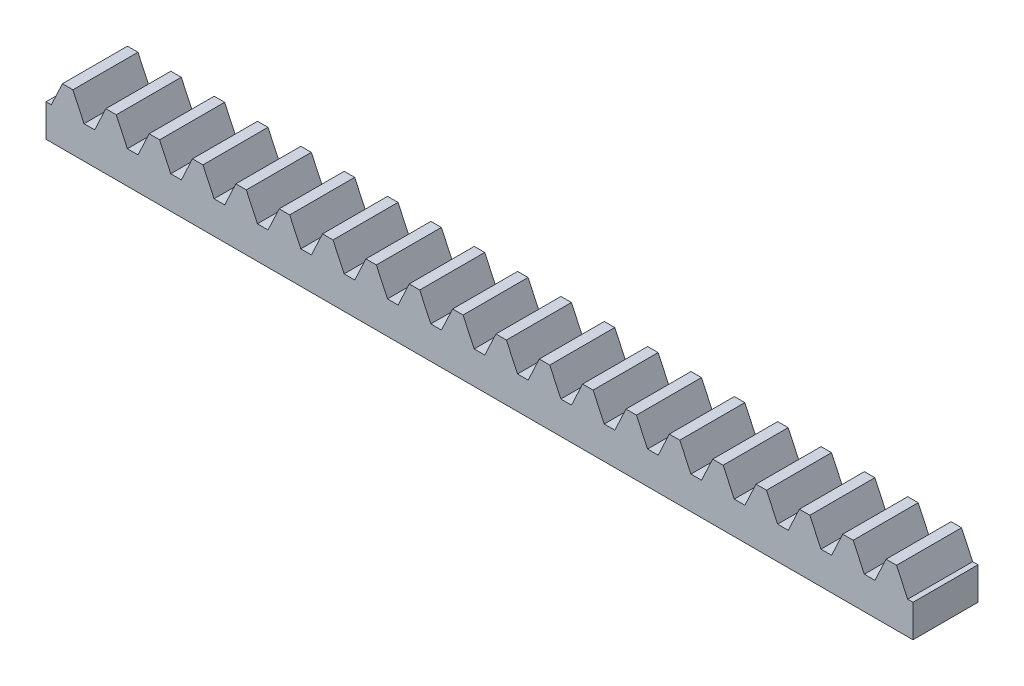
SolidWorks part; units mm, degrees
material "ABS"
ref_plane "Front Plane" through (0, 0, 0) normal (0, 0, 1) x (1, 0, 0)
ref_plane "Top Plane" through (0, 0, 0) normal (0, 1, 0) x (1, 0, 0)
ref_plane "Right Plane" through (0, 0, 0) normal (1, 0, 0) x (0, 0, -1)
sketch "Sketch1" plane through (0, 0, 0) normal (0, 0, 1) x (1, 0, 0)
  line L0 (0, -3) -> (0, 2.2) construction
  line L1 (-0.4837, 2.2) -> (0.4837, 2.2)
  line L2 (0.5337, 2.2) -> (1.5596, 0) construction
  line L4 (2, 0) -> (2, -3)
  line L5 (2, -3) -> (-2, -3)
  line L7 (0, 0.2) -> (2, 0.2) construction
  line L8 (2, 0.2) -> (2, 2.2) construction
  line L9 (2, 1.2) -> (0, 1.2) construction
  line L11 (2, 2.2) -> (0, 2.2) construction
  line L14 (0.4837, 2.2) -> (1.5096, 0)
  line L15 (2, 0) -> (1.5096, 0)
  line L16 (-2, 0) -> (-2, -3)
  line L17 (-2, 0) -> (-1.5096, 0)
  line L18 (-0.4837, 2.2) -> (-1.5096, 0)
  point P12 (1, 1.2)
  dimension "D3" = 2
  dimension "D4" = 155
  dimension "D5" = 4
  dimension "D1" = 0.2
  dimension "D2" = 3
  dimension "D6" = 0.05
extrude "Extrude Tooth" add sketch "Sketch1" along normal mid plane 6
pattern_linear "Pattern Teeth" count 20 spacing 4 along (1, 0, 0) of "Extrude Tooth"
equation "\"nTeeth\"=20"
equation "\"xThickness\"=6"
equation "\"xWall\"=3"
equation "\"aPressure\"=25"
equation "\"rHeight\"=2"
equation "\"pitch\"=4"
equation "\"rClearance\"=0.2"
equation "\"xClearance\"=0.05"
equation "\"D4@Sketch1\"=180-\"aPressure\""
equation "\"D5@Sketch1\"=\"pitch\""
equation "\"D6@Sketch1\"=\"xClearance\""
equation "\"D3@Sketch1\"=\"rHeight\""
equation "\"D1@Sketch1\"=\"rClearance\""
equation "\"D2@Sketch1\"=\"xWall\""
equation "\"D1@Pattern Teeth\" = \"nTeeth\""
equation "\"D1@Extrude Tooth\"=\"xThickness\""
